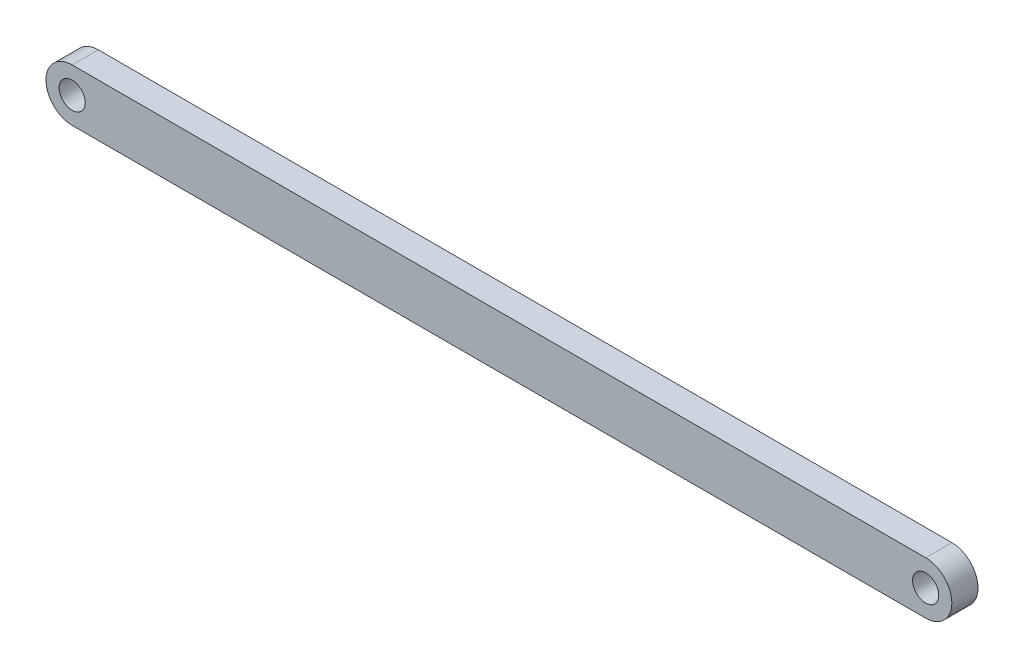
SolidWorks part; units mm, degrees
ref_plane "前视基准面" through (0, 0, 0) normal (0, 0, 1) x (1, 0, 0)
ref_plane "上视基准面" through (0, 0, 0) normal (0, 1, 0) x (1, 0, 0)
ref_plane "右视基准面" through (0, 0, 0) normal (1, 0, 0) x (0, 0, -1)
other "Configuration Table"
sketch "草图1" plane through (0, 0, 0) normal (0, 0, 1) x (1, 0, 0)
  line L0 (0, 5) -> (163, 5)
  line L1 (0, -5) -> (163, -5)
  circle A0 centre (0, 0) radius 2.5
  arc A1 (0, 5) -> (0, -5) centre (0, 0) ccw
  arc A4 (163, -5) -> (163, 5) centre (163, 0) ccw
  circle A5 centre (163, 0) radius 2.5
  dimension "D2" = 5
  dimension "D3" = 5
  dimension "D4" = 5
  dimension "D1" = 163
extrude "凸台-拉伸3" add sketch "草图1" along normal blind 5
